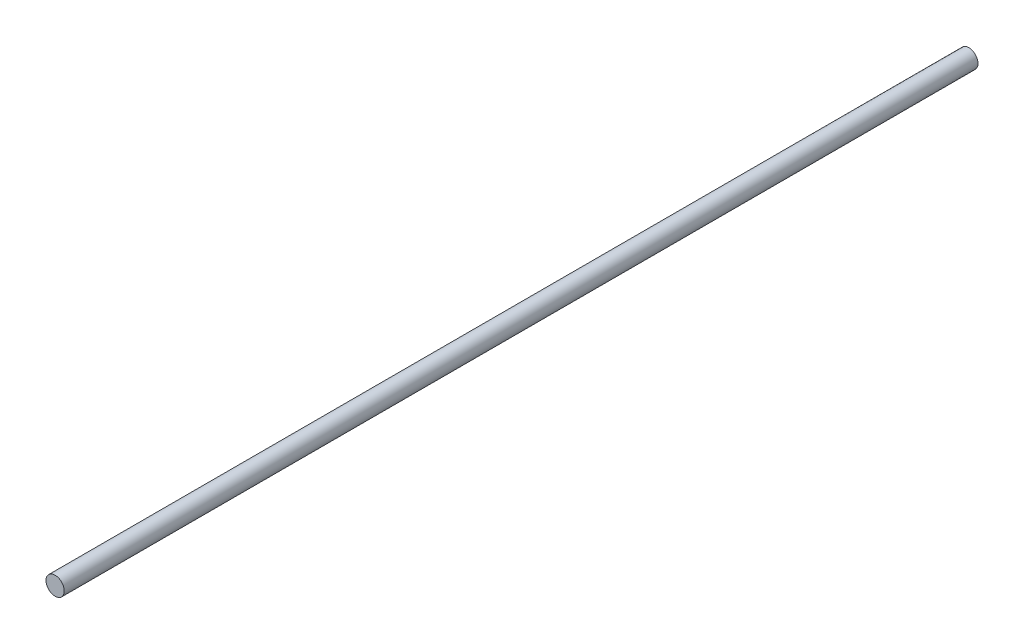
SolidWorks part; units mm, degrees
ref_plane "Front Plane" through (0, 0, 0) normal (0, 0, 1) x (1, 0, 0)
ref_plane "Top Plane" through (0, 0, 0) normal (0, 1, 0) x (1, 0, 0)
ref_plane "Right Plane" through (0, 0, 0) normal (1, 0, 0) x (0, 0, -1)
sketch "Sketch1" plane through (0, 0, 0) normal (0, 1, 0) x (1, 0, 0)
  line L0 (0, 50) -> (0, -50) construction
  dimension "D1" = 100
  dimension "D2" = 50
sketch "Sketch2" plane through (0, 0, 0) normal (0, 0, 1) x (1, 0, 0)
  circle A0 centre (0, 0) radius 1
  dimension "D1" = 2
extrude "Boss-Extrude1" add sketch "Sketch2" along normal mid plane 100
